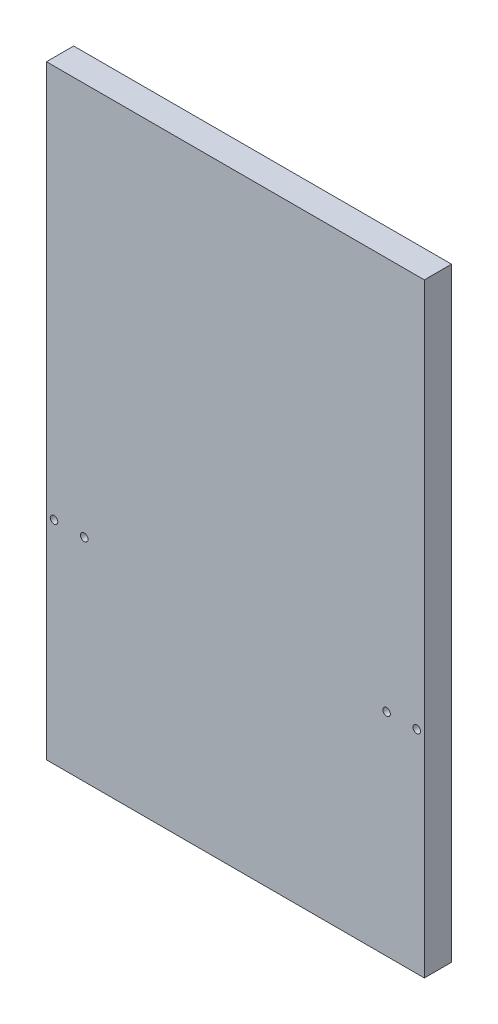
SolidWorks part; units mm, degrees
ref_plane "Plan de face" through (0, 0, 0) normal (0, 0, 1) x (1, 0, 0)
ref_plane "Plan de dessus" through (0, 0, 0) normal (0, 1, 0) x (1, 0, 0)
ref_plane "Plan de droite" through (0, 0, 0) normal (1, 0, 0) x (0, 0, -1)
sketch "Esquisse1" plane through (0, 0, 0) normal (0, 0, 1) x (1, 0, 0)
  line L5 (-808.9626, 140) -> (49191.0374, 140) construction
  line L6 (0, 0) -> (250, 0)
  line L7 (0, 0) -> (0, 400)
  line L8 (0, 400) -> (250, 400)
  line L9 (250, 0) -> (250, 400)
  circle A0 centre (245, 140) radius 2.5
  circle A1 centre (225, 140) radius 2.5
  circle A2 centre (5, 140) radius 2.5
  circle A3 centre (25, 140) radius 2.5
  dimension "D4" = 5
  dimension "D5" = 5
  dimension "D6" = 5
  dimension "D7" = 5
  dimension "D1" = 250
  dimension "D2" = 400
  dimension "D3" = 140
  dimension "D8" = 20
  dimension "D9" = 20
  dimension "D10" = 5
  dimension "D11" = 5
extrude "Boss.-Extru.1" add sketch "Esquisse1" along normal blind 18
